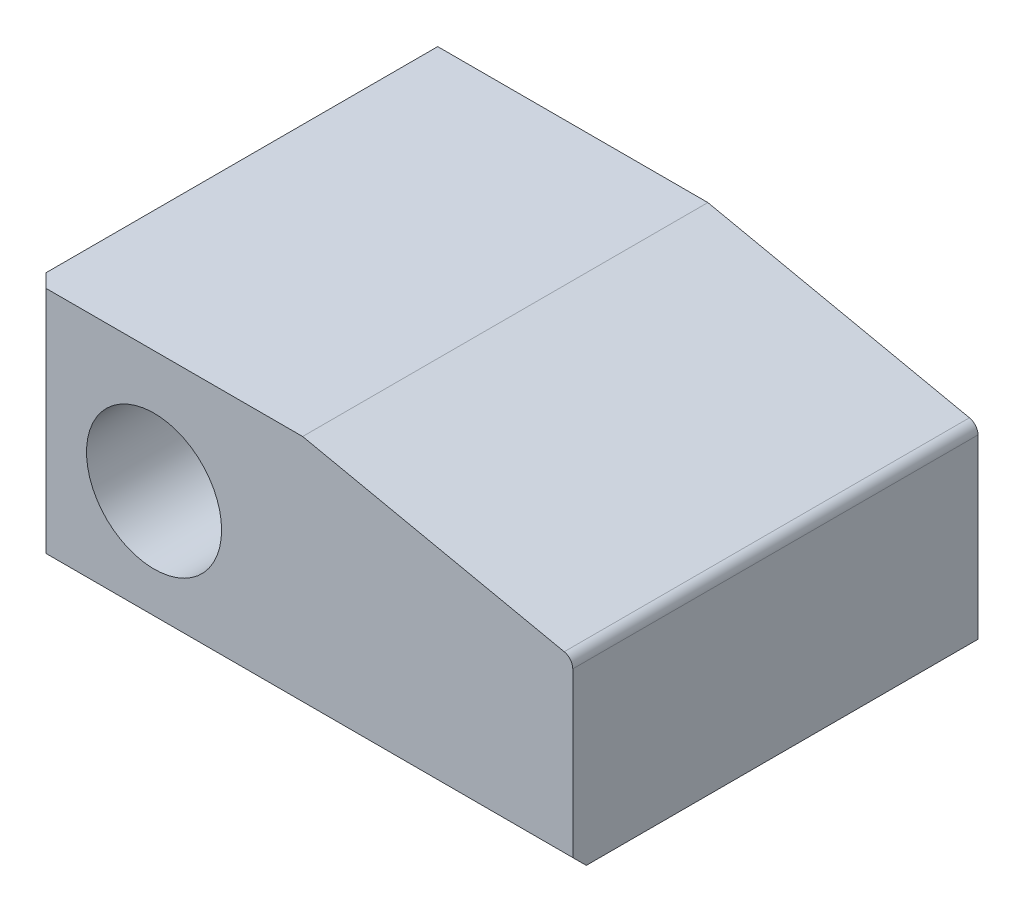
SolidWorks part; units mm, degrees
material "AISI Type A2 Tool Steel"
ref_plane "Front Plane" through (0, 0, 0) normal (0, 0, 1) x (1, 0, 0)
ref_plane "Top Plane" through (0, 0, 0) normal (0, 1, 0) x (1, 0, 0)
ref_plane "Right Plane" through (0, 0, 0) normal (1, 0, 0) x (0, 0, -1)
sketch "Sketch1" plane through (0, 0, 0) normal (0, 0, 1) x (1, 0, 0)
  line L0 (5.5, 4.5) -> (15.5, 2.3744)
  line L1 (-4.5, 4.5) -> (5.5, 4.5)
  line L2 (-4.5, 4.5) -> (-4.5, -4.5)
  line L3 (-4.5, -4.5) -> (15.5, -4.5)
  line L4 (15.5, 2.3744) -> (15.5, -4.5)
  line L5 (5.5, 4.5) -> (20, 4.5) construction
  circle A0 centre (0, 0) radius 2.5
  point P7 (-4.5, 0)
  dimension "D1" = 5
  dimension "D2" = 9
  dimension "D3" = 0
  dimension "D4" = 12
  dimension "D5" = 4.5
  dimension "D6" = 20
  dimension "D7" = 10
extrude "Boss-Extrude1" add sketch "Sketch1" along normal blind 15
fillet "Fillet1" radius 0.4 1 edges at (15.5, 2.3744, 7.5)
sketch "Sketch2" plane through (0, 0, 0) normal (0, 0, -1) x (-1, 0, 0)
  line L0 (4.5, -4.5) -> (-15.5, -4.5) construction
  line L1 (4.5, 4.5) -> (-9.5, 4.5)
  line L2 (4.5, 4.5) -> (4.5, -4.5)
  line L3 (4.5, -4.5) -> (-9.5, -4.5)
  line L4 (-9.5, 4.5) -> (-9.5, -4.5)
  dimension "D1" = 14
sketch "Sketch5" plane through (-4.5, 0, 0) normal (-1, 0, 0) x (0, 0, 1)
  line L0 (15, 4.5) -> (15, -4.5) construction
  circle A0 centre (12.25, 0) radius 2
  dimension "D1" = 4
  dimension "D2" = 2.75
chamfer "Chamfer2" distance 0.5 angle 45 2 edges at (5.5, -4.5, 15) (-4.5, 0, 15)
